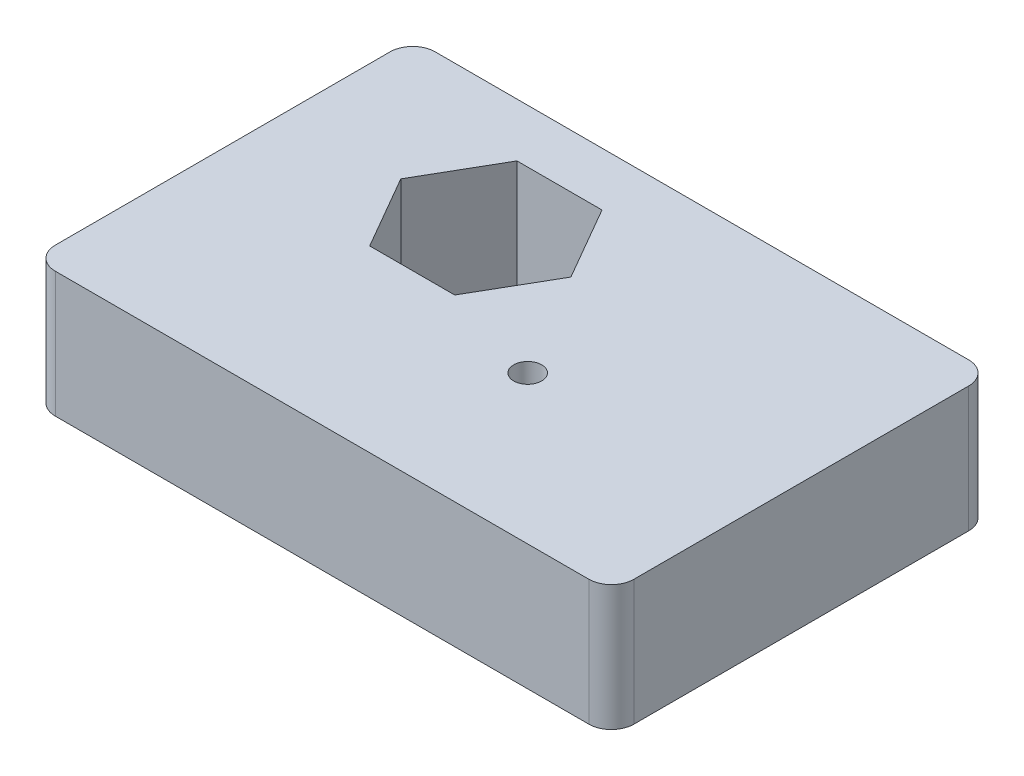
SolidWorks part; units mm, degrees
material "Balsa"
ref_plane "Front Plane" through (0, 0, 0) normal (0, 0, 1) x (1, 0, 0)
ref_plane "Top Plane" through (0, 0, 0) normal (0, 1, 0) x (1, 0, 0)
ref_plane "Right Plane" through (0, 0, 0) normal (1, 0, 0) x (0, 0, -1)
sketch "Sketch1" plane through (0, 0, 0) normal (0, 1, 0) x (1, 0, 0)
  line L1 (0, 0) -> (27.5, 0)
  line L2 (0, 0) -> (0, 18)
  line L3 (0, 18) -> (27.5, 18)
  line L4 (27.5, 0) -> (27.5, 18)
  line L5 (13.6569, 12) -> (11.5785, 15.6)
  line L6 (11.5785, 15.6) -> (7.4215, 15.6)
  line L7 (7.4215, 15.6) -> (5.3431, 12)
  line L8 (5.3431, 12) -> (7.4215, 8.4)
  line L9 (7.4215, 8.4) -> (11.5785, 8.4)
  line L10 (11.5785, 8.4) -> (13.6569, 12)
  circle A0 centre (9.5, 12) radius 1.75 construction
  circle A1 centre (16.5, 7) radius 0.75
  circle A2 centre (9.5, 12) radius 3.6 construction
  dimension "D3" = 1.5
  dimension "D4" = 3.5
  dimension "D1" = 27.5
  dimension "D2" = 18
  dimension "D5" = 9.5
  dimension "D6" = 6
  dimension "D7" = 7
  dimension "D8" = 16.5
  dimension "D9" = 7.2
extrude "Boss-Extrude1" add sketch "Sketch1" along normal blind 6
fillet "Fillet1" radius 1 4 edges at (0, 3, 0) (0, 3, -18) (27.5, 3, -18) (27.5, 3, 0)
other "Move Face1" face at (16.5, 6, -6.25) face at (12.6177, 3, -13.8) face at (9.5, 3, -15.6) face at (27.1036, 3, -0.3964) face at (27.5, 3, -9) face at (27.1036, 3, -17.6036) face at (13.75, 3, -18) face at (0.3964, 3, -17.6036) face at (0, 3, -9) face at (0.3964, 3, -0.3964) face at (13.75, 3, 0) face at (6.3823, 3, -13.8) face at (9.5, 3, -8.4) face at (6.3823, 3, -10.2) face at (12.6177, 3, -10.2) parameters "D1"=0.08
